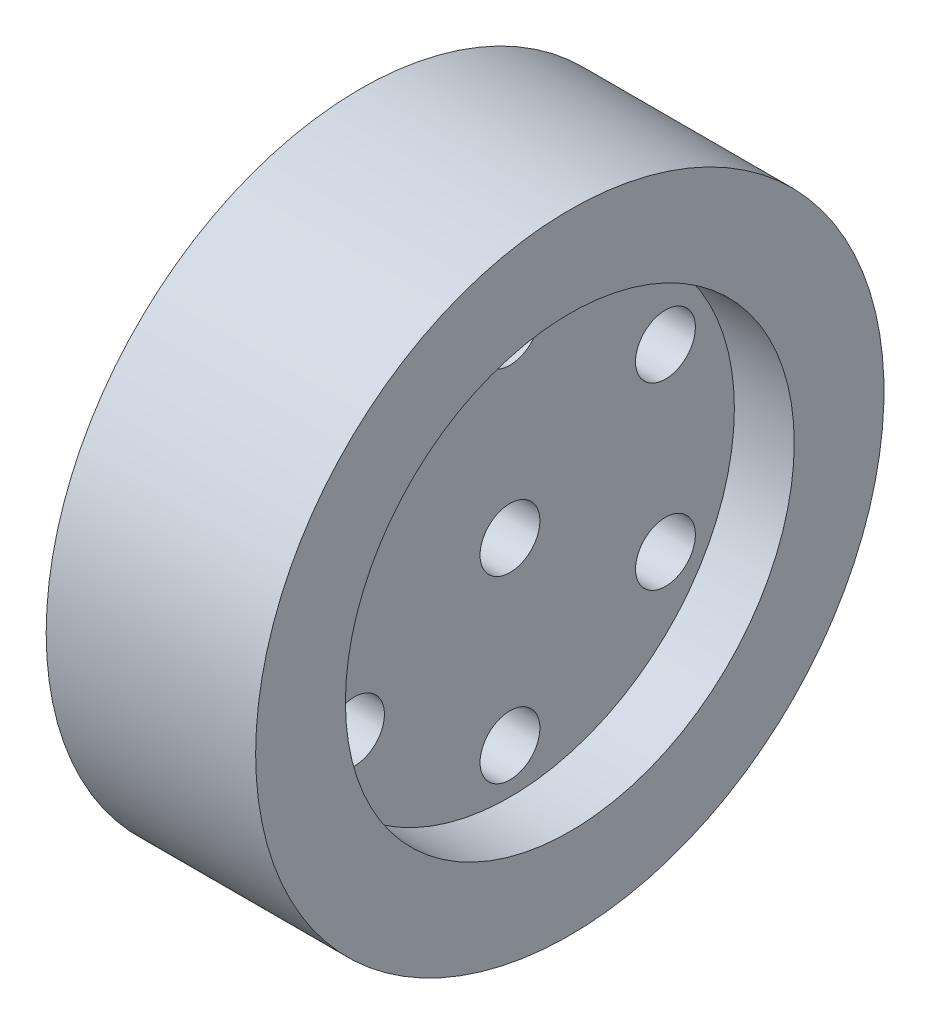
SolidWorks part; units mm, degrees
ref_plane "Front Plane" through (0, 0, 0) normal (0, 0, 1) x (1, 0, 0)
ref_plane "Top Plane" through (0, 0, 0) normal (0, 1, 0) x (1, 0, 0)
ref_plane "Right Plane" through (0, 0, 0) normal (1, 0, 0) x (0, 0, -1)
sketch "Sketch1" plane through (0, 0, 0) normal (0, 0, 1) x (1, 0, 0)
  line L0 (0, 0) -> (8904.9491, 0) construction
  line L1 (0, 0) -> (0, 8904.9491) construction
  line L2 (0, 2) -> (10, 2)
  line L3 (10, 2) -> (10, 15)
  line L4 (10, 15) -> (14, 15)
  line L5 (14, 15) -> (14, 21)
  line L6 (14, 21) -> (0, 21)
  line L7 (0, 21) -> (0, 19)
  line L8 (0, 19) -> (4, 19)
  line L9 (4, 19) -> (4, 5)
  line L10 (4, 5) -> (0, 5)
  line L11 (0, 5) -> (0, 2)
  dimension "D1" = 2
  dimension "D2" = 5
  dimension "D3" = 19
  dimension "D4" = 21
  dimension "D5" = 4
  dimension "D6" = 15
  dimension "D7" = 4
  dimension "D8" = 14
  dimension "D9" = 4
revolve "Revolve1" add sketch "Sketch1" angle 360 about L0
sketch "Sketch2" plane through (4, 0, 0) normal (-1, 0, 0) x (0, 0, 1)
  circle A0 centre (0, 0) radius 12 construction
  circle A1 centre (0, 12) radius 2
  circle A2 centre (10.3923, 6) radius 2
  circle A3 centre (10.3923, -6) radius 2
  circle A4 centre (0, -12) radius 2
  circle A5 centre (-10.3923, -6) radius 2
  circle A6 centre (-10.3923, 6) radius 2
  point P6 (12.2202, 5.3847)
  point P7 (0, 0)
  point P17 (0, 0)
  dimension "D1" = 24
  dimension "D2" = 4
  dimension "D3" = 6
extrude "Cut-Extrude1" cut sketch "Sketch2" against normal blind 50
